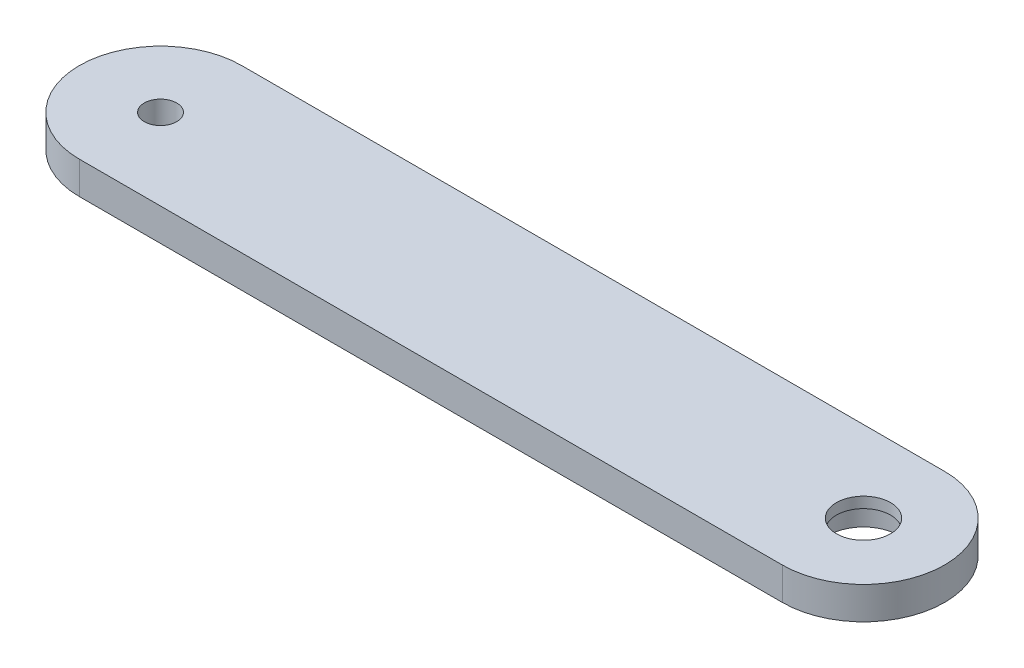
SolidWorks part; units mm, degrees
ref_plane "Front Plane" through (0, 0, 0) normal (0, 0, 1) x (1, 0, 0)
ref_plane "Top Plane" through (0, 0, 0) normal (0, 1, 0) x (1, 0, 0)
ref_plane "Right Plane" through (0, 0, 0) normal (1, 0, 0) x (0, 0, -1)
sketch "Sketch2" plane through (0, 0, 0) normal (0, 1, 0) x (1, 0, 0)
  line L1 (-6.5, 28.5) -> (123.5, 28.5)
  line L3 (-6.5, -1.5) -> (123.5, -1.5)
  arc A0 (-6.5, 28.5) -> (-6.5, -1.5) centre (-6.5, 13.5) ccw
  circle A1 centre (-6.5, 13.5) radius 3
  arc A2 (123.5, -1.5) -> (123.5, 28.5) centre (123.5, 13.5) ccw
  circle A3 centre (123.5, 13.5) radius 5
extrude "Boss-Extrude1" add sketch "Sketch2" along normal blind 6
sketch "Sketch4" plane through (0, 0, 0) normal (0, -1, 0) x (1, 0, 0)
  circle A0 centre (123.5, -13.5) radius 6.5
extrude "Cut-Extrude1" cut sketch "Sketch4" against normal blind 4
